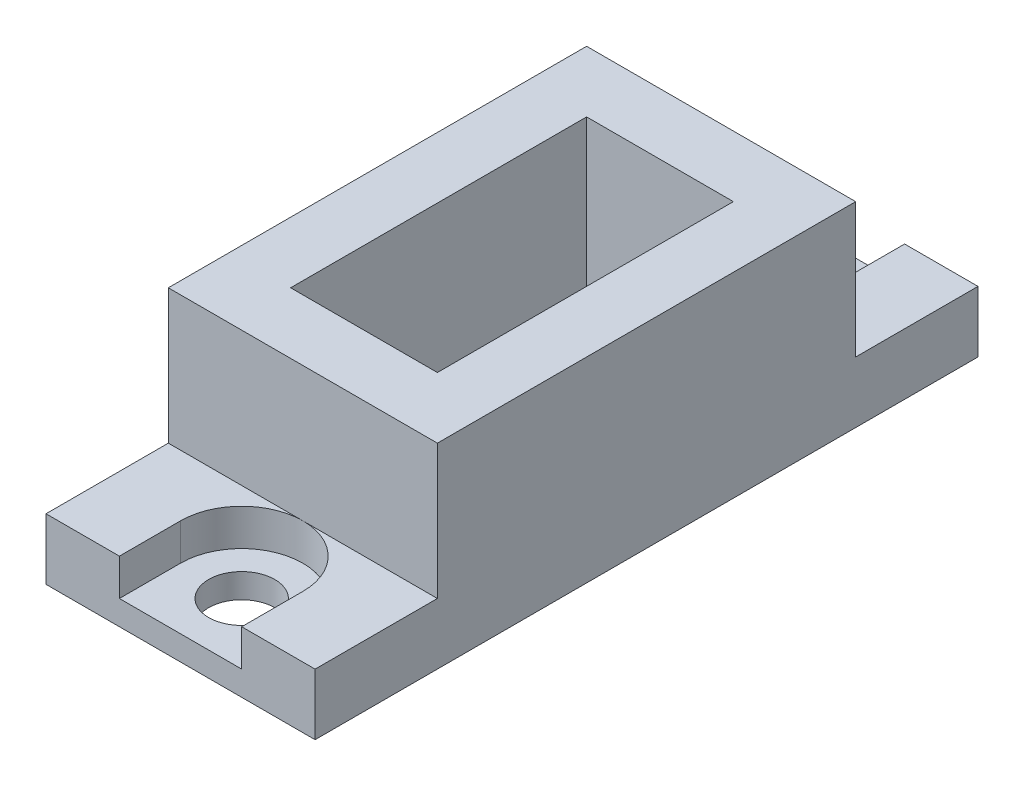
SolidWorks part; units mm, degrees
ref_plane "Front Plane" through (0, 0, 0) normal (0, 0, 1) x (1, 0, 0)
ref_plane "Top Plane" through (0, 0, 0) normal (0, 1, 0) x (1, 0, 0)
ref_plane "Right Plane" through (0, 0, 0) normal (1, 0, 0) x (0, 0, -1)
sketch "Sketch3" plane through (0, 0, 0) normal (0, 1, 0) x (1, 0, 0)
  line L0 (0, 2.0519) -> (0, 26.2519)
  line L1 (0, 26.2519) -> (12, 26.2519)
  line L2 (12, 26.2519) -> (12, 2.0519)
  line L3 (12, 2.0519) -> (0, 2.0519)
  line L9 (-5, 31.2519) -> (17, 31.2519)
  line L10 (-5, 31.2519) -> (-5, -2.9481)
  line L11 (-5, -2.9481) -> (17, -2.9481)
  line L12 (17, 31.2519) -> (17, -2.9481)
extrude "Boss-Extrude1" add sketch "Sketch3" along normal blind 16
sketch "Sketch4" plane through (0, 0, 0) normal (0, 1, 0) x (1, 0, 0)
  line L0 (-5, 31.2519) -> (-5, 41.2519)
  line L1 (17, 31.2519) -> (17, 41.2519)
  line L2 (17, 41.2519) -> (-5, 41.2519)
  line L3 (-5, 31.2519) -> (17, 31.2519)
  line L4 (-5, -2.9481) -> (-5, -12.9481)
  line L5 (17, -2.9481) -> (17, -12.9481)
  line L6 (17, -12.9481) -> (-5, -12.9481)
  line L7 (-5, -2.9481) -> (17, -2.9481)
extrude "Boss-Extrude2" add sketch "Sketch4" along normal blind 5
sketch "Sketch6" plane through (0, 5, 0) normal (0, 1, 0) x (1, 0, 0)
  line L0 (-5, -7.9481) -> (17, -7.9481)
  line L1 (-5, -2.9481) -> (-5, -12.9481) construction
  line L2 (17, -12.9481) -> (17, -2.9481) construction
  line L3 (-5, 36.2519) -> (17, 36.2519)
  line L4 (-5, 41.2519) -> (-5, 31.2519) construction
  line L5 (17, 31.2519) -> (17, 41.2519) construction
sketch "Sketch8" plane through (0, 5, 0) normal (0, 1, 0) x (1, 0, 0)
  line L0 (-5, 36.2519) -> (17, 36.2519) construction
  line L1 (-5, 31.2519) -> (17, 31.2519) construction
  line L2 (-5, -7.9481) -> (17, -7.9481) construction
  line L3 (-5, -2.9481) -> (17, -2.9481) construction
  line L4 (1, 36.2519) -> (1, 41.2519)
  line L5 (17, 41.2519) -> (-5, 41.2519) construction
  line L6 (1, 41.2519) -> (11, 41.2519)
  line L7 (11, 41.2519) -> (11, 36.2519)
  line L8 (1, -7.9481) -> (1, -12.9481)
  line L9 (-5, -12.9481) -> (17, -12.9481) construction
  line L10 (1, -12.9481) -> (11, -12.9481)
  line L11 (11, -12.9481) -> (11, -7.9481)
  arc A0 (6, 31.2519) -> (11, 36.2519) centre (6, 36.2519) ccw
  arc A1 (6, 31.2519) -> (1, 36.2519) centre (6, 36.2519) cw
  arc A2 (6, -2.9481) -> (11, -7.9481) centre (6, -7.9481) cw
  arc A3 (6, -2.9481) -> (1, -7.9481) centre (6, -7.9481) ccw
sketch "Sketch10" plane through (0, 0, 0) normal (0, -1, 0) x (-1, 0, 0)
  line L0 (5, -7.9481) -> (-17, -7.9481) construction
  line L1 (-1, -7.9481) -> (-1, -12.9481) construction
  line L2 (5, 36.2519) -> (-17, 36.2519) construction
  line L3 (-1, -7.9481) -> (-1, -12.9481)
  line L4 (-1, -12.9481) -> (-11, -12.9481)
  line L5 (-11, -12.9481) -> (-11, -7.9481)
  line L6 (-11, 36.2519) -> (-11, 41.2519)
  line L7 (-11, 41.2519) -> (-1, 41.2519)
  line L8 (-1, 41.2519) -> (-1, 36.2519)
  arc A0 (-11, -7.9481) -> (-1, -7.9481) centre (-6, -7.9481) cw
  arc A1 (-11, 36.2519) -> (-1, 36.2519) centre (-6, 36.2519) ccw
extrude "Cut-Extrude6" cut sketch "Sketch8" against normal blind 3
sketch "Sketch12" plane through (0, 0, 0) normal (0, -1, 0) x (1, 0, 0)
  line L0 (-5, 7.9481) -> (17, 7.9481) construction
  circle A0 centre (6, 7.9481) radius 2.7
  circle A1 centre (6, -36.2519) radius 2.7
extrude "Cut-Extrude7" cut sketch "Sketch12" against normal blind 3
sketch "Sketch14" plane through (0, 16, 0) normal (0, 1, 0) x (1, 0, 0)
  line L0 (6, 26.2519) -> (6, 21.2519)
  line L1 (12, 26.2519) -> (0, 26.2519) construction
  circle A0 centre (6, 21.2519) radius 2
